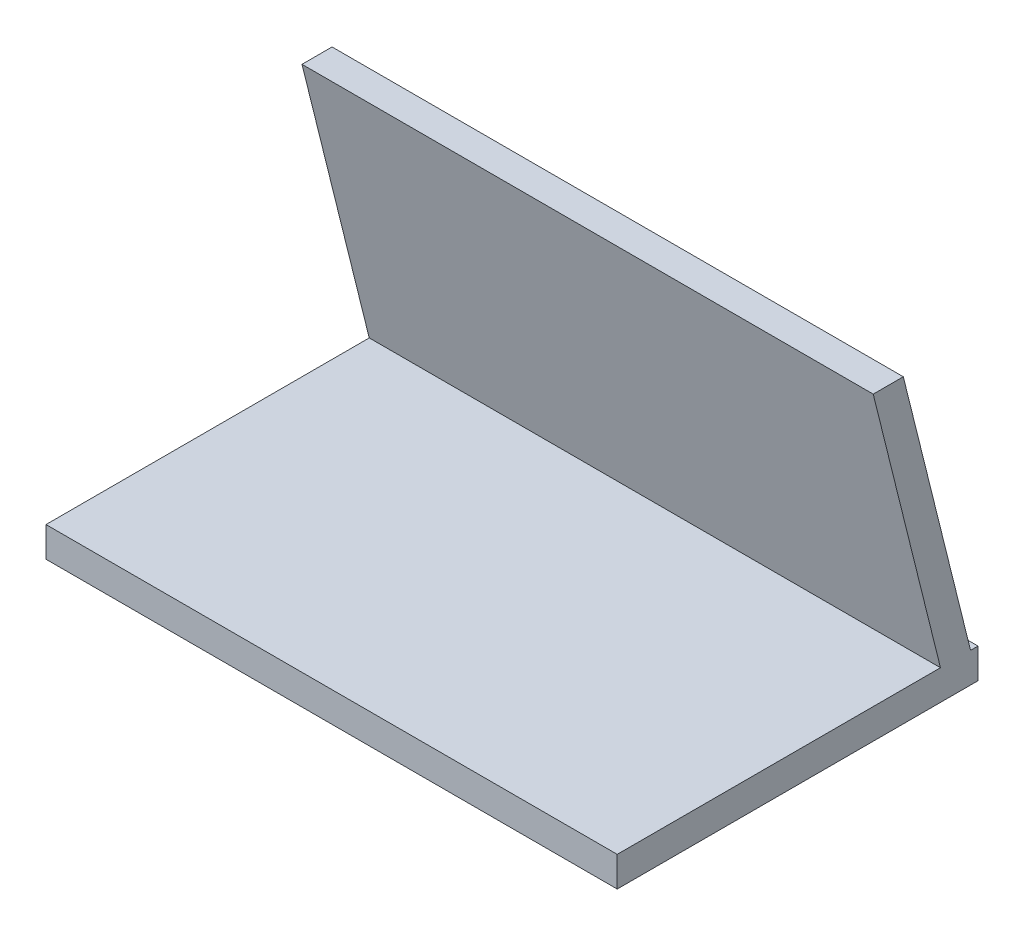
SolidWorks part; units mm, degrees
ref_plane "Front Plane" through (0, 0, 0) normal (0, 0, 1) x (1, 0, 0)
ref_plane "Top Plane" through (0, 0, 0) normal (0, 1, 0) x (1, 0, 0)
ref_plane "Right Plane" through (0, 0, 0) normal (1, 0, 0) x (0, 0, -1)
sketch "Sketch1" plane through (0, 0, 0) normal (0, 1, 0) x (1, 0, 0)
  line L1 (0, 0) -> (95, 0)
  line L2 (0, 0) -> (0, -60)
  line L3 (0, -60) -> (95, -60)
  line L4 (95, 0) -> (95, -60)
  dimension "D1" = 95
  dimension "D2" = 60
extrude "Boss-Extrude1" add sketch "Sketch1" along normal blind 5
sketch "Sketch6" plane through (0, 0, 0) normal (-1, 0, 0) x (0, 0, 1)
  line L0 (0, 0) -> (12.4245, 50)
  line L1 (16.182, 45) -> (5, 0)
  line L2 (12.4245, 50) -> (17.4245, 50)
  line L4 (0, 0) -> (60, 0) construction
  line L6 (16.182, 45) -> (17.4245, 50)
  line L10 (0, 0) -> (60, 0)
  line L11 (60, 0) -> (60, 5)
  line L12 (60, 5) -> (0, 5)
  line L13 (0, 5) -> (0, 0)
  line L14 (0, 0) -> (5, 0)
  dimension "D1" = 50
  dimension "D3" = 0
  dimension "D4" = 5
extrude "Boss-Extrude3" add sketch "Sketch6" against normal blind 95
